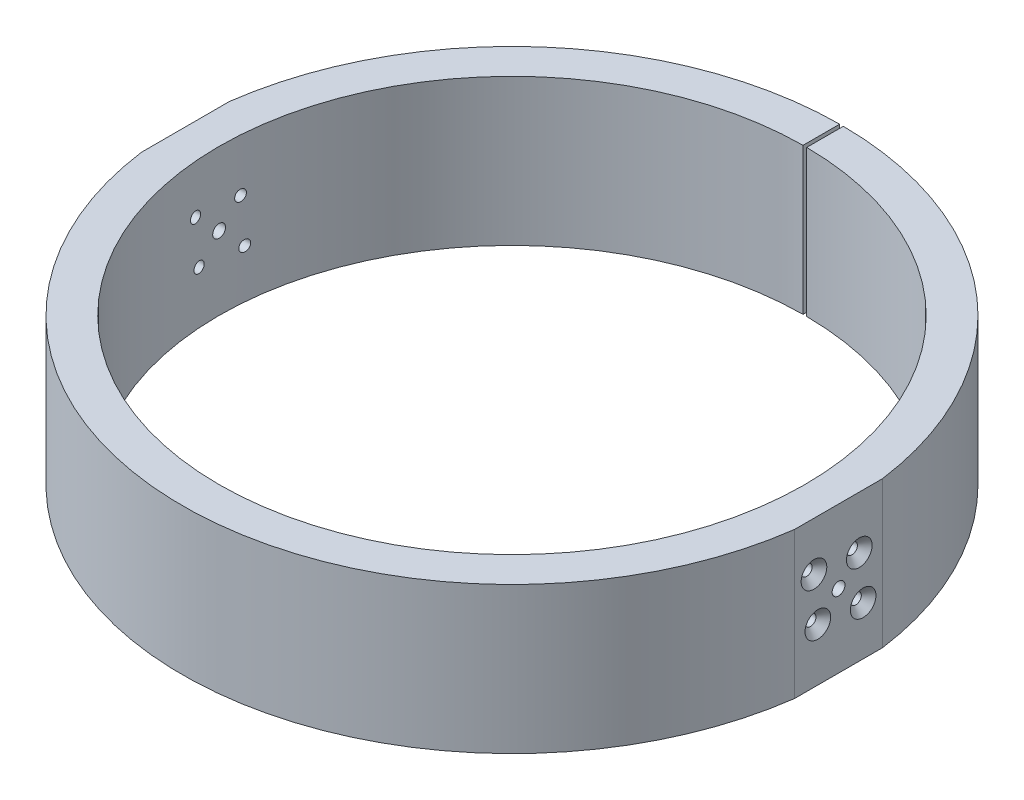
SolidWorks part; units mm, degrees
ref_plane "Front Plane" through (0, 0, 0) normal (0, 0, 1) x (1, 0, 0)
ref_plane "Top Plane" through (0, 0, 0) normal (0, 1, 0) x (1, 0, 0)
ref_plane "Right Plane" through (0, 0, 0) normal (1, 0, 0) x (0, 0, -1)
sketch "Sketch1" plane through (0, 0, 0) normal (0, 1, 0) x (1, 0, 0)
  circle A0 centre (0, 0) radius 90
  circle A1 centre (0, 0) radius 80
  dimension "D1" = 180
  dimension "D2" = 10
extrude "Boss-Extrude1" add sketch "Sketch1" along normal blind 40
sketch "Sketch2" plane through (0, 40, 0) normal (0, 1, 0) x (1, 0, 0)
  line L0 (-89.1964, 12) -> (-89.1964, -12)
  line L1 (0, 106.4921) -> (0, -119.978) construction
  line L2 (0, 0) -> (-123.5613, 0) construction
  line L3 (89.1964, 12) -> (89.1964, -12)
  arc A0 (-89.1964, 12) -> (-89.1964, -12) centre (0, 0) ccw
  circle A1 centre (0, 0) radius 90 construction
  arc A2 (89.1964, 12) -> (89.1964, -12) centre (0, 0) cw
  dimension "D1" = 12
extrude "Cut-Extrude1" cut sketch "Sketch2" against normal blind 70
sketch "Sketch3" plane through (-89.1964, 0, 0) normal (-1, 0, 0) x (0, 0, 1)
  line L0 (-12, 40) -> (12, 0) construction
  line L1 (0, 20) -> (12.9792, 32.9792) construction
  line L2 (0, 20) -> (-12.9792, 32.9792) construction
  circle A0 centre (6.7175, 26.7175) radius 1.5
  circle A1 centre (-5.6569, 25.6569) radius 1.5
  circle A2 centre (-6.7175, 13.2825) radius 1.5
  circle A3 centre (5.6569, 14.3431) radius 1.5
  circle A4 centre (0, 20) radius 1.75
  dimension "D4" = 3
  dimension "D5" = 3.5
  dimension "D1" = 90
  dimension "D2" = 9.5
  dimension "D3" = 8
extrude "Cut-Extrude2" cut sketch "Sketch3" against normal blind 212
chamfer "Chamfer1" distance 2 angle 45 8 edges at (89.1964, 13.2825, -5.2175) (89.1964, 14.3431, 7.1569) (89.1964, 25.6569, -4.1569) (89.1964, 26.7175, 8.2175) (-89.1964, 13.2825, -8.2175) (-89.1964, 14.3431, 4.1569) (-89.1964, 26.7175, 8.2175) (-89.1964, 25.6569, -4.1569)
sketch "Sketch4" plane through (0, 0, 0) normal (0, 1, 0) x (1, 0, 0)
  line L1 (0.5, 5.598) -> (-0.5, 5.598)
  line L2 (0.5, 5.598) -> (0.5, 92.3665)
  line L3 (0.5, 92.3665) -> (-0.5, 92.3665)
  line L4 (-0.5, 5.598) -> (-0.5, 92.3665)
  line L5 (0.5, 5.598) -> (-0.5, 92.3665) construction
  line L6 (0.5, 92.3665) -> (-0.5, 5.598) construction
  point P0 (0, 48.9822)
  dimension "D1" = 1
extrude "Cut-Extrude4" cut sketch "Sketch4" against normal blind 10 and the other way through all
